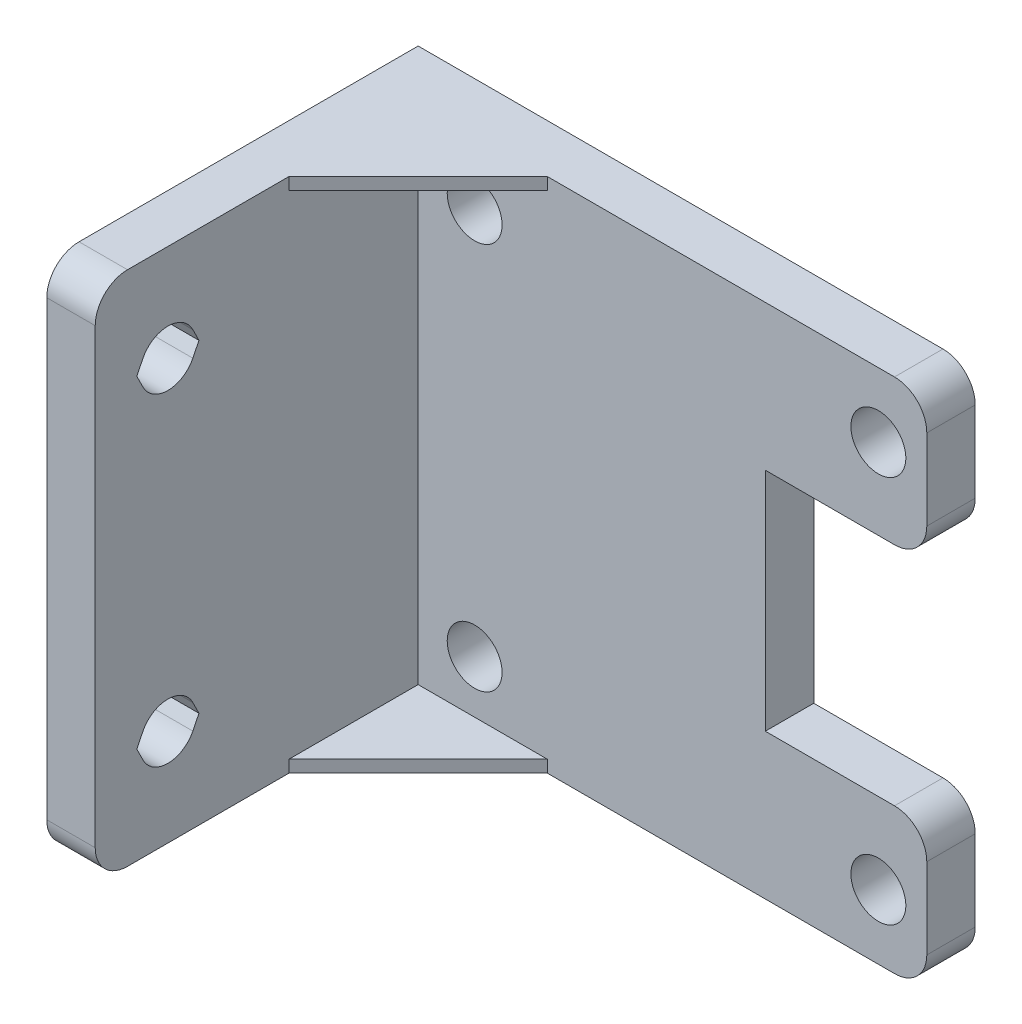
SolidWorks part; units mm, degrees
ref_plane "Front Plane" through (0, 0, 0) normal (0, 0, 1) x (1, 0, 0)
ref_plane "Top Plane" through (0, 0, 0) normal (0, 1, 0) x (1, 0, 0)
ref_plane "Right Plane" through (0, 0, 0) normal (1, 0, 0) x (0, 0, -1)
sketch "Sketch2" plane through (0, 0, 0) normal (0, 0, 1) x (1, 0, 0)
  line L0 (-12.5, 30) -> (-12.5, 0) construction
  line L1 (-28, 31) -> (3, 31)
  line L2 (-28, 31) -> (-28, -1)
  line L3 (-28, -1) -> (3, -1)
  line L4 (3, 31) -> (3, -1)
  line L5 (-25, 30) -> (0, 30) construction
  line L6 (0, 0) -> (-25, 0) construction
  line L7 (-25, 15) -> (0, 15) construction
  line L8 (-25, 4.7) -> (-25, 25.3) construction
  line L9 (0, 9) -> (0, 21) construction
  line L10 (3, 8) -> (-7, 8)
  line L11 (-7, 8) -> (-7, 22)
  line L12 (-7, 22) -> (3, 22)
  line L14 (-28, -1) -> (-31, -1)
  line L15 (-28, -1) -> (-28, 31)
  line L16 (-28, 31) -> (-31, 31)
  line L17 (0, 9) -> (0, 21)
  line L18 (0, 21) -> (-6, 21)
  line L19 (-6, 21) -> (-6, 9)
  line L20 (-6, 9) -> (0, 9)
  line L21 (0, 9) -> (0, 21) construction
  line L22 (0, 21) -> (-6, 21) construction
  line L23 (-6, 21) -> (-6, 9) construction
  line L24 (-6, 9) -> (0, 9) construction
  line L25 (-31, -1) -> (-31, 31)
  point P17 (3, 15)
  point P18 (-12.5, 31)
  point P24 (-7, 15)
  arc M6 (0, 1.3) -> (0, 4.7) centre (0, 3) cw
  line M7 (0, 4.7) -> (0, 9)
  arc M8 (0, 25.3) -> (0, 28.7) centre (0, 27) cw
  line M9 (0, 28.7) -> (0, 30)
  line M10 (0, 30) -> (-25, 30)
  line M11 (-25, 30) -> (-25, 28.7)
  arc M12 (-25, 28.7) -> (-25, 25.3) centre (-25, 27) cw
  line M13 (-25, 25.3) -> (-25, 4.7)
  arc M14 (-25, 4.7) -> (-25, 1.3) centre (-25, 3) cw
  line M15 (-25, 1.3) -> (-25, 0)
  line M16 (-25, 0) -> (0, 0)
  line M17 (0, 0) -> (0, 1.3)
  dimension "D1" = 1
  dimension "D2" = 3
  dimension "D3" = 0
  dimension "D4" = 1
  dimension "D5" = 1
  dimension "D6" = 3
extrude "Boss-Extrude1" add sketch "Sketch2" along normal blind 3 contours M17 M6 M7 M8 M9 M10 M11 M12 M13 M14 M15 M16 | L4 L1 L2 L3 M6 M17 M16 M15 M14 M13 M12 M11 M10 M9 M8 M7 | L25 L14 L2 L16
hole_wizard "M3 Clearance Hole1" positions "Sketch5" profile "Sketch6" hole size "M3" standard "ANSI Metric" end condition through all
sketch "Sketch5" plane through (0, 0, 0) normal (0, 0, -1) x (-1, 0, 0)
  point P1 (25, 3)
  point P3 (25, 27)
  point P5 (0, 27)
  point P7 (0, 3)
sketch "Sketch6" plane through (-25, 3, 0) normal (1, 0, 0) x (0, 1, 0)
  line L0 (0, 0) -> (0, 3)
  line L1 (0, 3) -> (1.7, 3)
  line L2 (1.7, 3) -> (1.7, 0.025)
  line L3 (1.7, 0.025) -> (1.725, 0)
  line L5 (1.725, 0) -> (0, 0)
  line L6 (-1.7, 0.025) -> (-1.725, 0) construction
  line L11 (0, -6.35) -> (0, 107.95) construction
  dimension "Thru Hole Dia." = 3.4
  dimension "Thru Hole Depth" = 3
  dimension "Near C'Sink Dia." = 3.45
  dimension "Near C'Sink Angle" = 90
sketch "Sketch7" plane through (0, 0, 3) normal (0, 0, 1) x (1, 0, 0)
  line L6 (-31, -1) -> (3, -1) construction
  line L7 (-28.5, -1) -> (-31.5, -1)
  line L8 (-28.5, -1) -> (-28.5, 31)
  line L9 (-28.5, 31) -> (-31.5, 31)
  line L10 (-31.5, -1) -> (-31.5, 31)
  line L11 (-31, 31) -> (3, 31) construction
  circle A1 centre (-25, 3) radius 1.7 construction
  dimension "D2" = 3.5
  dimension "D1" = 3
extrude "Boss-Extrude2" add sketch "Sketch7" along normal blind 20 and the other way up to surface other way up to face at (-26.725, 3, 0)
hole_wizard "M3 Clearance Hole2" positions "Sketch8" profile "Sketch9" hole size "M3" standard "ANSI Metric" end condition through all
sketch "Sketch8" plane through (-28.5, 27.5, 0) normal (1, 0, 0) x (0, -1, 0)
  line L3 (12.5, -23) -> (12.5, -3) construction
  line L9 (28.5, -3) -> (-3.5, -3) construction
  line L10 (28.5, -3) -> (-3.5, -3) construction
  line L11 (28.5, -23) -> (-3.5, -23) construction
  line L12 (28.5, -23) -> (-3.5, -23) construction
  point P11 (2.5, -18.5)
  point P21 (22.5, -18.5)
  point P38 (12.5, -3)
  dimension "D1" = 4.5
  dimension "D2" = 10
sketch "Sketch9" plane through (-28.5, 5, 18.5) normal (0, 1, 0) x (0, 0, -1)
  line L0 (0, 0) -> (0, 3)
  line L1 (0, 3) -> (1.7, 3)
  line L2 (1.7, 3) -> (1.7, 0.025)
  line L3 (1.7, 0.025) -> (1.725, 0)
  line L5 (1.725, 0) -> (0, 0)
  line L6 (-1.7, 0.025) -> (-1.725, 0) construction
  line L11 (0, -6.35) -> (0, 107.95) construction
  dimension "Thru Hole Dia." = 3.4
  dimension "Thru Hole Depth" = 3
  dimension "Near C'Sink Dia." = 3.45
  dimension "Near C'Sink Angle" = 90
fillet "Fillet1" radius 2 6 edges at (3, 8, 1.5) (3, 22, 1.5) (3, 31, 1.5) (-30, -1, 23) (-30, 31, 23) (3, -1, 1.5)
sketch "Sketch11" plane through (0, -1, 0) normal (0, -1, 0) x (1, 0, 0)
  line L0 (-28.5, 11) -> (-20.5, 3)
  line L1 (-28.5, 3) -> (-28.5, 21) construction
  line L2 (-28.5, 3) -> (1, 3) construction
  line L3 (-28.5, 3) -> (1, 3) construction
  dimension "D1" = 45
  dimension "D2" = 8
rib "Rib1" sketch "Sketch11" sketch "Sketch11" thickness 0.75 extrusion direction parallel to sketch draft on no parameters "D1"=0.75
ref_plane "Plane1" through (0, 15, 0) normal (0, 1, 0) x (1, 0, 0)
mirror "Mirror1" about plane through (0, 15, 0) normal (0, 1, 0) of "Rib1"
sketch "Sketch12" plane through (-28.5, 0, 0) normal (1, 0, 0) x (0, 0, -1)
  line L0 (-20.0458, 4.2344) -> (-20.425, 5)
  line L1 (-20.425, 5) -> (-20.0458, 5.7656)
  line L2 (-18.5, 6.725) -> (-18.5, 3.275) construction
  line L3 (-16.575, 5) -> (-16.9542, 5.7656)
  line L4 (-16.9542, 4.2344) -> (-16.575, 5)
  line L5 (-20.0458, 24.2344) -> (-20.425, 25)
  line L6 (-20.425, 25) -> (-20.0458, 25.7656)
  line L7 (-16.575, 25) -> (-16.9542, 25.7656)
  line L8 (-16.9542, 24.2344) -> (-16.575, 25)
  circle A0 centre (-18.5, 25) radius 1.725 construction
  circle A1 centre (-18.5, 5) radius 1.725 construction
  circle A2 centre (-18.5, 25) radius 1.725
  circle A3 centre (-18.5, 5) radius 1.725
  point P10 (-20.225, 5)
  point P19 (-20.225, 25)
  point P22 (0, 0)
  circle M18 centre (-18.5, 25) radius 1.725
  circle M19 centre (-18.5, 5) radius 1.725
  dimension "D1" = 0.2
  dimension "D2" = 0.2
extrude "Cut-Extrude1" cut sketch "Sketch12" against normal through all contours L1 L0 M19 | L4 L3 M19 | L8 L7 M18 | L6 L5 M18 | M18 | A3 L2 M19 | L2 A3 M19
